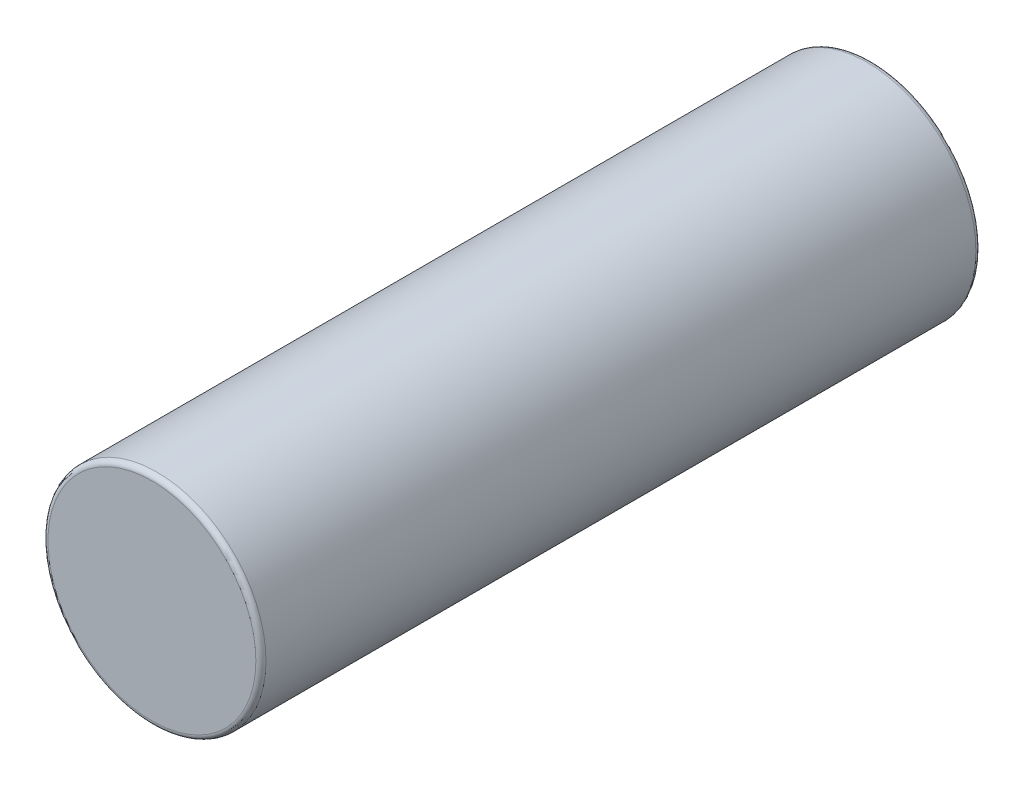
SolidWorks part; units mm, degrees
ref_plane "Ebene vorne" through (0, 0, 0) normal (0, 0, 1) x (1, 0, 0)
ref_plane "Ebene oben" through (0, 0, 0) normal (0, 1, 0) x (1, 0, 0)
ref_plane "Ebene rechts" through (0, 0, 0) normal (1, 0, 0) x (0, 0, -1)
sketch "Skizze1" plane through (0, 0, 0) normal (0, 0, 1) x (1, 0, 0)
  circle A0 centre (156.4322, 44.2671) radius 10.75
  dimension "D1" = 21.5
extrude "Aufsatz-Linear austragen1" add sketch "Skizze1" along normal blind 71
fillet "Verrundung1" radius 0.5 2 edges at (167.1822, 44.2671, 0) (167.1822, 44.2671, 71)
